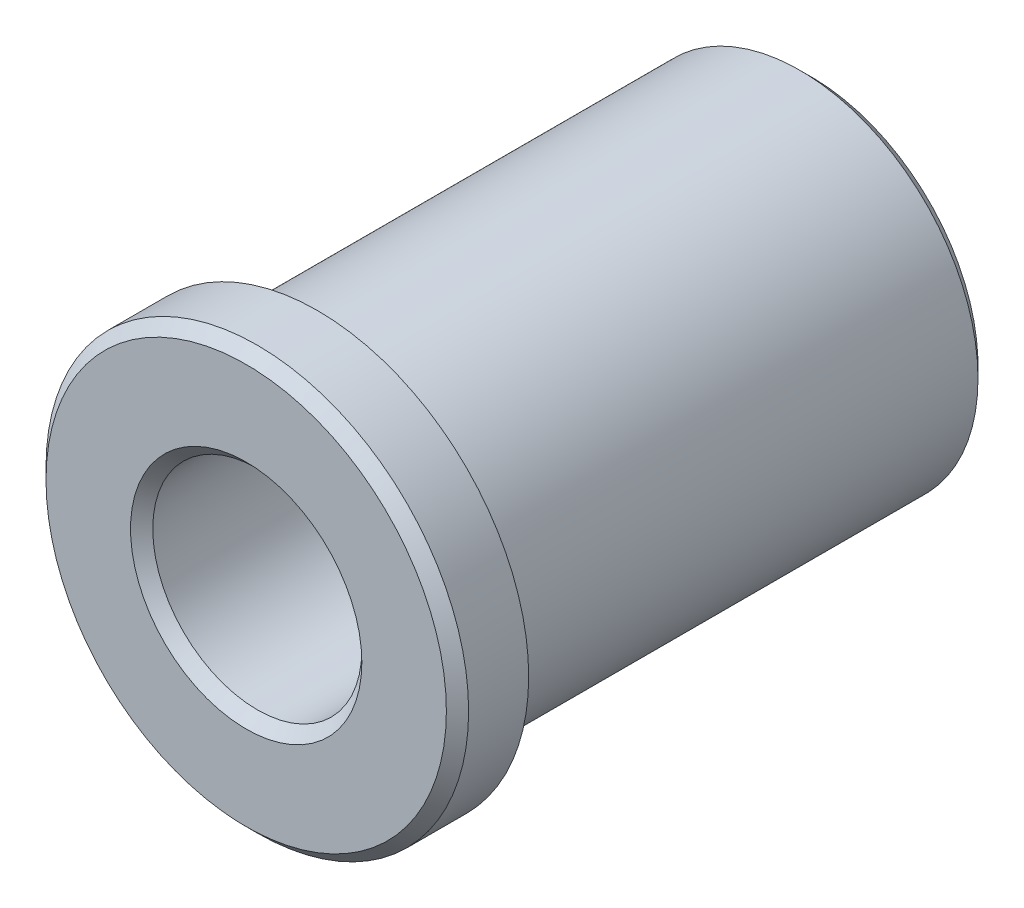
SolidWorks part; units mm, degrees
other "Defeature"
material "Aluminum Bronze"
ref_plane "Front Plane" through (0, 0, 0) normal (0, 0, 1) x (1, 0, 0)
ref_plane "Top Plane" through (0, 0, 0) normal (0, 1, 0) x (1, 0, 0)
ref_plane "Right Plane" through (0, 0, 0) normal (1, 0, 0) x (0, 0, -1)
sketch "Sketch6" plane through (0, 0, 0) normal (0, 1, 0) x (1, 0, 0)
  line L0 (0, 0) -> (0, 12.7) construction
  line L1 (2.35, 0) -> (4.75, 0)
  line L2 (4.75, 0) -> (4.75, 1.6)
  line L3 (4.75, 1.6) -> (4, 1.6)
  line L4 (4, 1.6) -> (4, 12.7)
  line L5 (4, 12.7) -> (2.35, 12.7)
  line L6 (2.35, 12.7) -> (2.35, 0)
  dimension "D1" = 8
  dimension "D2" = 9.5
  dimension "D3" = 4.7
  dimension "D4" = 1.6
  dimension "D5" = 12.7
revolve "Revolve1" add sketch "Sketch6" angle 360 about L0
chamfer "Chamfer1" distance 0.25 angle 45 4 edges at (2.35, 0, 0) (4.75, 0, 0) (4, 0, -12.7) (2.35, 0, -12.7)
